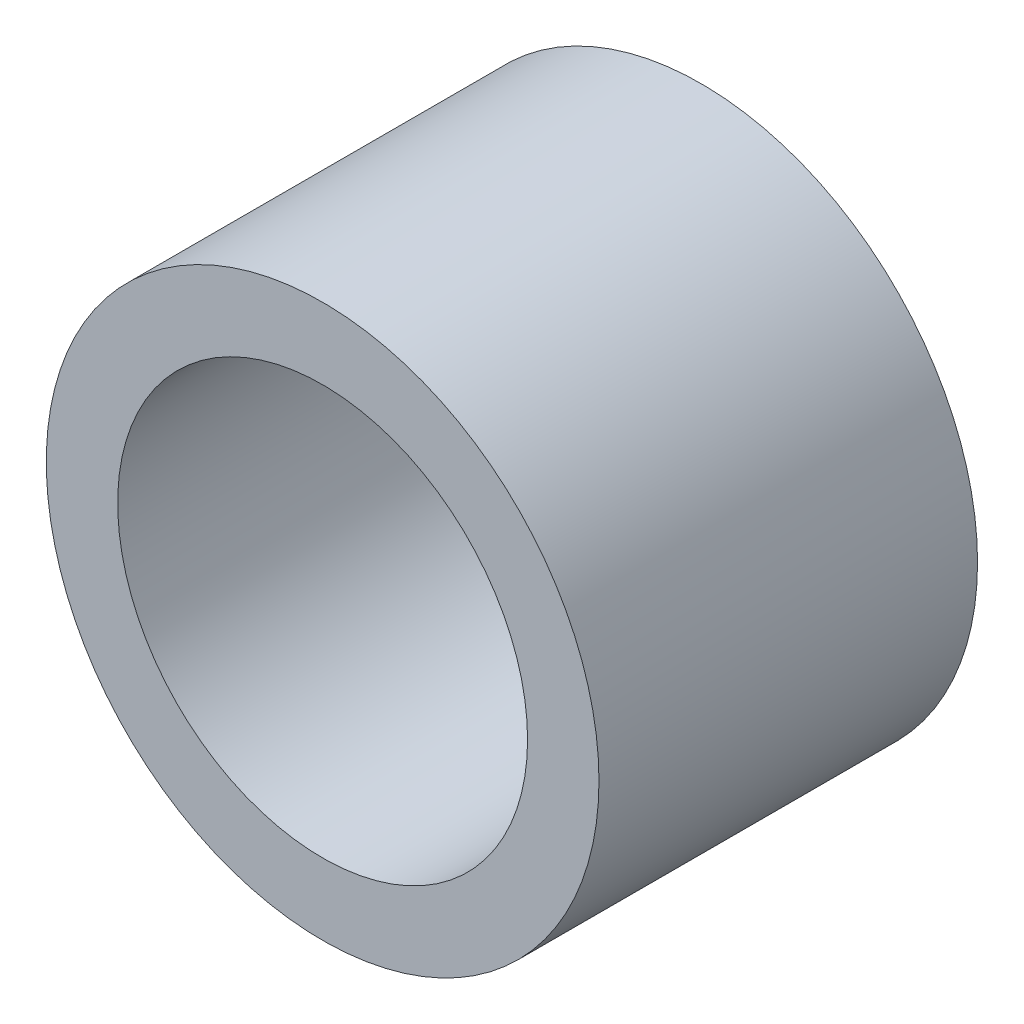
SolidWorks part; units mm, degrees
material "Alloy Steel"
ref_plane "Front Plane" through (0, 0, 0) normal (0, 0, 1) x (1, 0, 0)
ref_plane "Top Plane" through (0, 0, 0) normal (0, 1, 0) x (1, 0, 0)
ref_plane "Right Plane" through (0, 0, 0) normal (1, 0, 0) x (0, 0, -1)
sketch "Sketch1" plane through (0, 0, 0) normal (0, 0, 1) x (1, 0, 0)
  circle A9 centre (0, 0) radius 9.271
  circle A10 centre (0, 0) radius 6.8758
  dimension "D1" = 18.542
  dimension "D2" = 13.7516
extrude "Boss-Extrude1" add sketch "Sketch1" along normal blind 12.7
